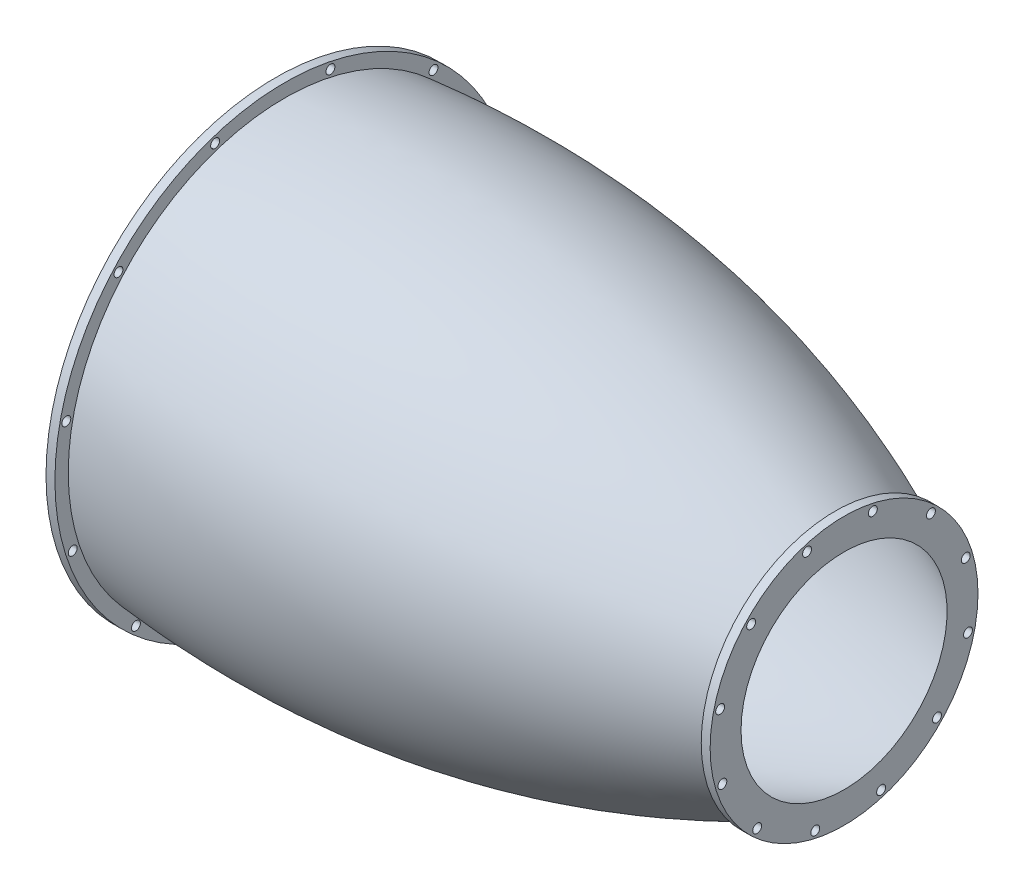
SolidWorks part; units mm, degrees
material "Copper"
ref_plane "Front Plane" through (0, 0, 0) normal (0, 0, 1) x (1, 0, 0)
ref_plane "Top Plane" through (0, 0, 0) normal (0, 1, 0) x (1, 0, 0)
ref_plane "Right Plane" through (0, 0, 0) normal (1, 0, 0) x (0, 0, -1)
sketch "Sketch1" plane through (0, 0, 0) normal (0, 0, 1) x (1, 0, 0)
  line L0 (-1229.8282, 0) -> (1426.3964, 0) construction
  line L1 (0, -70.104) -> (0, 70.104) construction
  line L2 (0, 0) -> (500, 0) construction
  line L3 (500, -330.2) -> (500, 330.2) construction
  line L5 (500, 339.09) -> (500, 330.2)
  line L6 (0, -78.994) -> (0, -70.104)
  line L7 (500, -339.09) -> (500, -330.2)
  line L8 (-412.8242, -144.8099) -> (-412.8242, 144.8099) construction
  line L9 (-412.8242, 144.8099) -> (-412.8242, 153.6999)
  line L10 (-412.8242, -144.8099) -> (-412.8242, -153.6999)
  spline S0 degree 2 poles (0, 70.104) (170.2621, 318.867) (500, 330.2) knots 0 0 0 1 1 1
  spline S1 degree 2 poles (0, -70.104) (170.2621, -318.867) (500, -330.2) knots 0 0 0 1 1 1
  spline S2 degree 2 poles (0, -78.994) (170.2621, -327.757) (500, -339.09) knots 0 0 0 1 1 1
  spline S3 degree 2 poles (0, -70.104) (170.2621, -318.867) (500, -330.2) knots 0 0 0 1 1 1
  spline S4 degree 2 poles (0, 78.994) (170.2621, 327.757) (500, 339.09) knots 0 0 0 1 1 1
  spline S5 degree 2 poles (0, 70.104) (-195.4497, 157.4108) (-412.8242, 144.8099) knots 0 0 0 1 1 1
  spline S6 degree 2 poles (0, -70.104) (-195.4497, -157.4108) (-412.8242, -144.8099) knots 0 0 0 1 1 1
  spline S7 degree 2 poles (0, -78.994) (-192.7304, -176.7061) (-412.8242, -153.6999) knots 0 0 0 1 1 1
  spline S9 degree 2 poles (0, 78.994) (-192.7304, 176.7061) (-412.8242, 153.6999) knots 0 0 0 1 1 1
  point P8 (0, 0)
  point P14 (500, 0)
  point P22 (-412.8242, 0)
  dimension "D4" = 8.89
  dimension "D1" = 140.208
  dimension "D2" = 500
  dimension "D3" = 660.4
  dimension "D5" = 8.89
  dimension "D6" = 8.89
  dimension "D7" = 289.6197
revolve "Revolve3" add sketch "Sketch1" angle 360 about L0
ref_plane "Plane1" through (0, 0, 0) normal (1, 0, 0) x (0, 0, -1)
ref_plane "Plane2" through (-7.62, 0, 0) normal (-1, 0, 0) x (0, 0, 1)
sketch "Sketch4" plane through (-7.62, 0, 0) normal (-1, 0, 0) x (0, 0, 1)
  line L1 (-1213.2286, 638.9142) -> (1085.9115, 638.9142)
  line L2 (-1213.2286, 638.9142) -> (-1213.2286, -445.9528)
  line L3 (-1213.2286, -445.9528) -> (1085.9115, -445.9528)
  line L4 (1085.9115, 638.9142) -> (1085.9115, -445.9528)
extrude "Cut-Extrude1" cut sketch "Sketch4" against normal blind 782.066
ref_plane "Plane3" through (-7.62, 0, 0) normal (1, 0, 0) x (0, 0, -1)
sketch "Sketch5" plane through (-7.62, 0, 0) normal (1, 0, 0) x (0, 0, -1)
  circle A0 centre (0, 0) radius 82.8048 construction
  circle A1 centre (0, 0) radius 82.8048
  circle A2 centre (0, 0) radius 95.5048
  dimension "D1" = 12.7
extrude "Boss-Extrude1" add sketch "Sketch5" against normal blind 6.35
ref_plane "Plane4" through (-412.8242, 0, 0) normal (-1, 0, 0) x (0, 0, 1)
sketch "Sketch6" plane through (-412.8242, 0, 0) normal (-1, 0, 0) x (0, 0, 1)
  circle A0 centre (0, 0) radius 153.6999 construction
  circle A1 centre (0, 0) radius 153.6999
  circle A2 centre (0, 0) radius 163.8599
  dimension "D1" = 10.16
extrude "Boss-Extrude2" add sketch "Sketch6" against normal blind 6.35 contours A2 | A1
ref_plane "Plane5" through (-13.97, 0, 0) normal (-1, 0, 0) x (0, 0, 1)
sketch "Sketch7" plane through (-13.97, 0, 0) normal (-1, 0, 0) x (0, 0, 1)
  line L0 (0, 0) -> (21.6047, -93.0291) construction
  line L1 (21.6047, -93.0291) -> (19.4321, -83.674) construction
  circle A1 centre (0, 0) radius 95.5048
  circle A2 centre (0, 0) radius 95.5048
  circle A3 centre (0, 0) radius 85.9007 construction
  circle A4 centre (0, 0) radius 85.9007
  point P7 (20.5184, -88.3515)
  dimension "D1" = 0
hole_wizard "1/4 (0.25) Diameter Hole1" positions "3DSketch1" profile "Sketch8" hole size "1/4" standard "ANSI Inch"
sketch3d "3DSketch1"
  point P0 (-13.97, -88.3515, 20.5184)
sketch "Sketch8" plane through (-13.97, -88.3515, 20.5184) normal (0, 1, 0) x (0, 0, 1)
  line L0 (0, 0) -> (0, 8.2577)
  line L1 (0, 8.2577) -> (3.175, 6.35)
  line L2 (3.175, 6.35) -> (3.175, 0)
  line L5 (3.175, 0) -> (0, 0)
  line L10 (0, 8.2577) -> (-3.175, 6.35) construction
  line L11 (0, -6.35) -> (0, 107.95) construction
  dimension "Hole Dia." = 6.35
  dimension "Hole Depth" = 6.35
  dimension "Drill Angle" = 118
pattern_circular "CirPattern1" count 12 over 360 about axis through (0, 0, 0) along (1, 0, 0) of "1/4 (0.25) Diameter Hole1"
ref_plane "Plane6" through (-406.4742, 0, 0) normal (1, 0, 0) x (0, 0, -1)
sketch "Sketch9" plane through (-406.4742, 0, 0) normal (1, 0, 0) x (0, 0, -1)
  line L0 (0, 0) -> (-33.5856, -160.381) construction
  line L1 (-33.5856, -160.381) -> (-31.6341, -151.0623) construction
  circle A0 centre (0, 0) radius 163.8599 construction
  circle A1 centre (0, 0) radius 163.8599
  circle A2 centre (0, 0) radius 154.3391 construction
  circle A3 centre (0, 0) radius 154.3391
  point P6 (-32.6098, -155.7217)
hole_wizard "1/4 (0.25) Diameter Hole2" positions "3DSketch2" profile "Sketch10" hole size "1/4" standard "ANSI Inch"
sketch3d "3DSketch2"
  point P0 (-406.4742, -155.7217, 32.6098)
sketch "Sketch10" plane through (-406.4742, -155.7217, 32.6098) normal (0, 1, 0) x (0, 0, -1)
  line L0 (0, 0) -> (0, 8.2577)
  line L1 (0, 8.2577) -> (3.175, 6.35)
  line L2 (3.175, 6.35) -> (3.175, 0)
  line L5 (3.175, 0) -> (0, 0)
  line L10 (0, 8.2577) -> (-3.175, 6.35) construction
  line L11 (0, -6.35) -> (0, 107.95) construction
  dimension "Hole Dia." = 6.35
  dimension "Hole Depth" = 6.35
  dimension "Drill Angle" = 118
pattern_circular "CirPattern2" count 12 over 360 about axis through (0, 0, 0) along (1, 0, 0) of "1/4 (0.25) Diameter Hole2"
